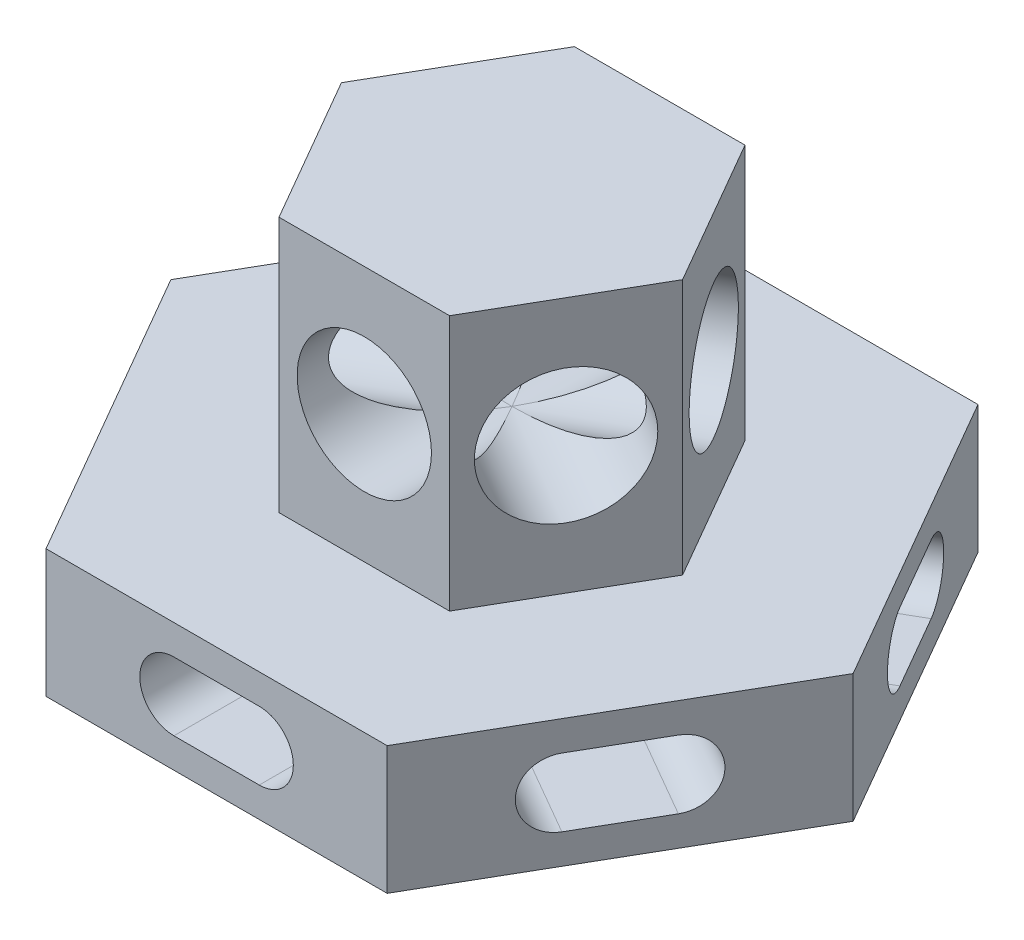
SolidWorks part; units mm, degrees
ref_plane "Front Plane" through (0, 0, 0) normal (0, 0, 1) x (1, 0, 0)
ref_plane "Top Plane" through (0, 0, 0) normal (0, 1, 0) x (1, 0, 0)
ref_plane "Right Plane" through (0, 0, 0) normal (1, 0, 0) x (0, 0, -1)
sketch "Sketch1" plane through (0, 0, 0) normal (0, 1, 0) x (1, 0, 0)
  line L1 (40, -69.282) -> (80, 0)
  line L2 (80, 0) -> (40, 69.282)
  line L3 (40, 69.282) -> (-40, 69.282)
  line L4 (-40, 69.282) -> (-80, 0)
  line L5 (-80, 0) -> (-40, -69.282)
  line L6 (-40, -69.282) -> (40, -69.282)
  circle A0 centre (0, 0) radius 69.282 construction
  point P1 (0, 0)
  dimension "D1" = 80
extrude "Boss-Extrude1" add sketch "Sketch1" along normal blind 30
sketch "Sketch2" plane through (0, 30, 0) normal (0, 1, 0) x (1, 0, 0)
  line L1 (20, -34.641) -> (40, 0)
  line L2 (40, 0) -> (20, 34.641)
  line L3 (20, 34.641) -> (-20, 34.641)
  line L4 (-20, 34.641) -> (-40, 0)
  line L5 (-40, 0) -> (-20, -34.641)
  line L6 (-20, -34.641) -> (20, -34.641)
  circle A0 centre (0, 0) radius 34.641 construction
  point P1 (40, -1.6807)
  dimension "D1" = 40
extrude "Boss-Extrude2" add sketch "Sketch2" along normal blind 60
hole_wizard "Hole1" positions "Sketch3" profile "Sketch4" legacy end condition through all
sketch "Sketch3" plane through (0, 0, 34.641) normal (0, 0, 1) x (1, 0, 0)
  line L0 (-20, 90) -> (20, 90) construction
  point P0 (0, 60)
  point P5 (0, 0)
  dimension "D1" = 30
sketch "Sketch4" plane through (0, 60, 34.641) normal (1, 0, 0) x (0, -1, 0)
  line L0 (0, 0) -> (0, 103.923)
  line L1 (0, 103.923) -> (15.75, 103.923)
  line L2 (15.75, 103.923) -> (15.75, 0)
  line L3 (15.75, 0) -> (0, 0)
  line L4 (0, 110) -> (0, -10) construction
  dimension "Diameter" = 31.5
  dimension "Depth" = 103.923
pattern_circular "CirPattern2" count 6 over 360 about axis through (0, 90, 0) along (0, 1, 0) of "Hole1"
sketch "Sketch5" plane through (0, 0, 69.282) normal (0, 0, 1) x (1, 0, 0)
  line L0 (-10, 15) -> (10, 15) construction
  line L1 (-10, 23) -> (10, 23)
  line L2 (-10, 7) -> (10, 7)
  line L3 (-40, 30) -> (40, 30) construction
  arc A0 (-10, 23) -> (-10, 7) centre (-10, 15) ccw
  arc A1 (10, 7) -> (10, 23) centre (10, 15) ccw
  point P2 (0, 15)
  point P7 (0, 0)
  dimension "D1" = 8
  dimension "D2" = 20
  dimension "D3" = 15
extrude "Cut-Extrude1" cut sketch "Sketch5" against normal through all and the other way through all
pattern_circular "CirPattern3" count 6 over 360 about axis through (0, 90, 0) along (0, 1, 0) of "Cut-Extrude1"
